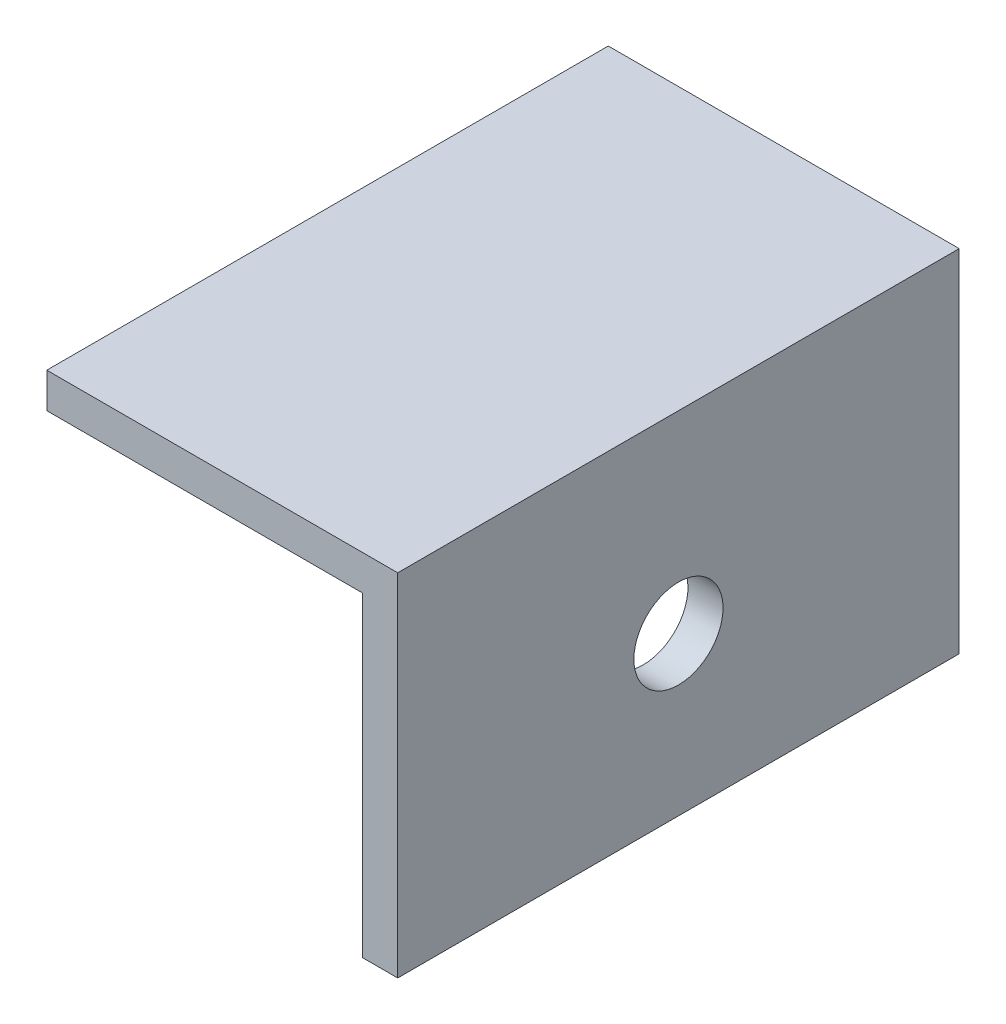
SolidWorks part; units mm, degrees
ref_plane "Alzado" through (0, 0, 0) normal (0, 0, 1) x (1, 0, 0)
ref_plane "Planta" through (0, 0, 0) normal (0, 1, 0) x (1, 0, 0)
ref_plane "Vista lateral" through (0, 0, 0) normal (1, 0, 0) x (0, 0, -1)
sketch "Croquis1" plane through (0, 0, 0) normal (0, 0, 1) x (1, 0, 0)
  line L0 (0, 0) -> (0, 50)
  line L1 (0, 50) -> (-50, 50)
  line L2 (-50, 50) -> (-50, 45)
  line L3 (-50, 45) -> (-5, 45)
  line L4 (-5, 45) -> (-5, 0)
  line L5 (-5, 0) -> (0, 0)
  dimension "D1" = 5
  dimension "D2" = 5
  dimension "D3" = 50
  dimension "D4" = 50
extrude "Saliente-Extruir1" add sketch "Croquis1" along normal blind 80
sketch "Croquis2" plane through (-5, 0, 0) normal (-1, 0, 0) x (0, 0, 1)
  line L0 (0, 45) -> (0, 0) construction
  line L1 (80, 0) -> (0, 0) construction
  circle A0 centre (40, 22.5) radius 6.35
  dimension "D2" = 12.7
  dimension "D1" = 40
  dimension "D3" = 22.5
extrude "Cortar-Extruir1" cut sketch "Croquis2" against normal up to next
